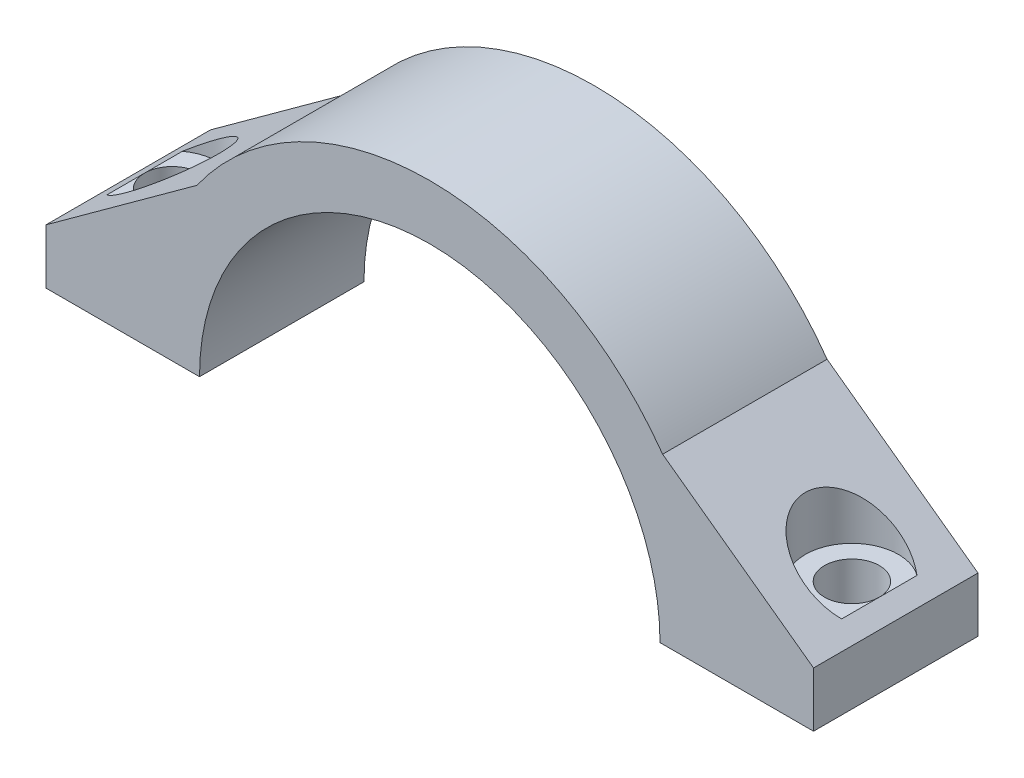
SolidWorks part; units mm, degrees
ref_plane "Alzado" through (0, 0, 0) normal (0, 0, 1) x (1, 0, 0)
ref_plane "Planta" through (0, 0, 0) normal (0, 1, 0) x (1, 0, 0)
ref_plane "Vista lateral" through (0, 0, 0) normal (1, 0, 0) x (0, 0, -1)
sketch "Croquis1" plane through (0, 0, 0) normal (0, 0, 1) x (1, 0, 0)
  line L0 (-26, 0) -> (-21, 0)
  line L5 (21, 0) -> (26, 0)
  arc A0 (26, 0) -> (-26, 0) centre (0, 0) ccw
  arc A2 (21, 0) -> (-21, 0) centre (0, 0) ccw
  point P0 (0, 0)
  dimension "D3" = 21
  dimension "D2" = 26
  dimension "D1" = 52
extrude "Saliente-Extruir1" add sketch "Croquis1" along normal mid plane 15
sketch "Croquis2" plane through (0, 0, 0) normal (0, 0, 1) x (1, 0, 0)
  line L0 (26, 0) -> (35, 0)
  line L1 (35, 0) -> (35, 5)
  line L2 (35, 5) -> (21.2368, 15)
  arc A0 (26, 0) -> (-26, 0) centre (0, 0) ccw construction
  arc A1 (26, 0) -> (21.2368, 15) centre (0, 0) ccw
  dimension "D1" = 9
  dimension "D2" = 5
  dimension "D3" = 15
extrude "Saliente-Extruir2" add sketch "Croquis2" along normal mid plane 15
sketch "Croquis3" plane through (0, 0, 0) normal (0, -1, 0) x (1, 0, 0)
  line L0 (21, -7.5) -> (35, -7.5) construction
  line L1 (35, 7.5) -> (35, -7.5) construction
  circle A0 centre (31, 0) radius 2.5
  point P6 (32.9215, -1.0297)
  dimension "D3" = 5
  dimension "D1" = 7.5
  dimension "D2" = 4
extrude "Cortar-Extruir1" cut sketch "Croquis3" against normal through all
ref_plane "Plano1" through (0, 6.09, 0) normal (0, -1, 0) x (-1, 0, 0)
sketch "Croquis4" plane through (0, 6.09, 0) normal (0, -1, 0) x (-1, 0, 0)
  circle A0 centre (-31, 0) radius 4.25
  dimension "D1" = 8.5
extrude "Cortar-Extruir2" cut sketch "Croquis4" against normal through all
mirror "Simetría1" about plane through (0, 0, 0) normal (1, 0, 0) of "Cortar-Extruir2", "Saliente-Extruir2", "Cortar-Extruir1"
